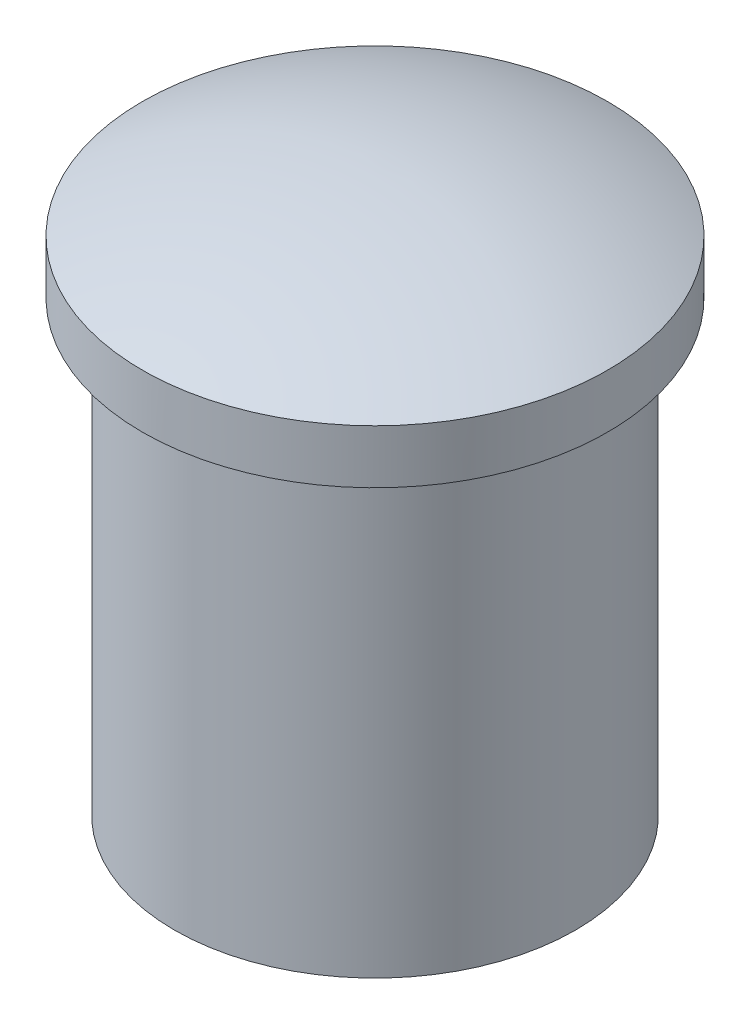
SolidWorks part; units mm, degrees
ref_plane "Front Plane" through (0, 0, 0) normal (0, 0, 1) x (1, 0, 0)
ref_plane "Top Plane" through (0, 0, 0) normal (0, 1, 0) x (1, 0, 0)
ref_plane "Right Plane" through (0, 0, 0) normal (1, 0, 0) x (0, 0, -1)
sketch "Sketch1" plane through (0, 0, 0) normal (0, 0, 1) x (1, 0, 0)
  line L0 (-1.651, 0.381) -> (1.651, 0.381) construction
  line L1 (0, -3.175) -> (1.4224, -3.175) construction
  line L2 (-1.4224, -3.175) -> (-1.4224, 0) construction
  line L3 (-1.4224, 0) -> (1.4224, 0) construction
  line L4 (1.4224, -3.175) -> (1.4224, 0) construction
  line L5 (-1.4224, -3.175) -> (1.4224, 0) construction
  line L6 (-1.4224, 0) -> (1.4224, -3.175) construction
  line L7 (-1.651, 0.762) -> (1.651, 0.762) construction
  line L8 (-1.651, 0.762) -> (-1.651, 0) construction
  line L9 (-1.651, 0) -> (1.651, 0) construction
  line L10 (1.651, 0.762) -> (1.651, 0) construction
  line L11 (-1.651, 0.762) -> (1.651, 0) construction
  line L12 (-1.651, 0) -> (1.651, 0.762) construction
  line L13 (-1.651, 0.381) -> (-1.651, 0)
  line L14 (-1.651, 0) -> (-1.4224, 0)
  line L15 (-1.4224, 0) -> (-1.4224, -3.175)
  line L16 (-1.4224, -3.175) -> (0, -3.175) construction
  line L17 (0, -2.7686) -> (0, 0.762)
  line L18 (-1.4224, -3.175) -> (0, -3.175) construction
  line L19 (0, -3.175) -> (0, -2.7686) construction
  arc A0 (-1.651, 0.381) -> (0, 0.762) centre (0, -3.0057) cw
  arc A1 (-1.4224, -3.175) -> (0, -2.7686) centre (0, -5.461) cw
  arc A2 (0, -2.7686) -> (1.4224, -3.175) centre (0, -5.461) cw construction
  point P0 (0, -1.5875)
  point P5 (0, 0)
  point P7 (0, 0.381)
  point P12 (0, 0)
  point P19 (-0.0655, -2.7277)
  point P20 (0, 0)
  point P21 (0, 0)
  point P23 (0, 0)
  dimension "D5" = 2.6924
  dimension "D1" = 3.175
  dimension "D2" = 2.8448
  dimension "D3" = 0.762
  dimension "D4" = 3.302
revolve "Revolve1" add sketch "Sketch1" angle 360 about L17
